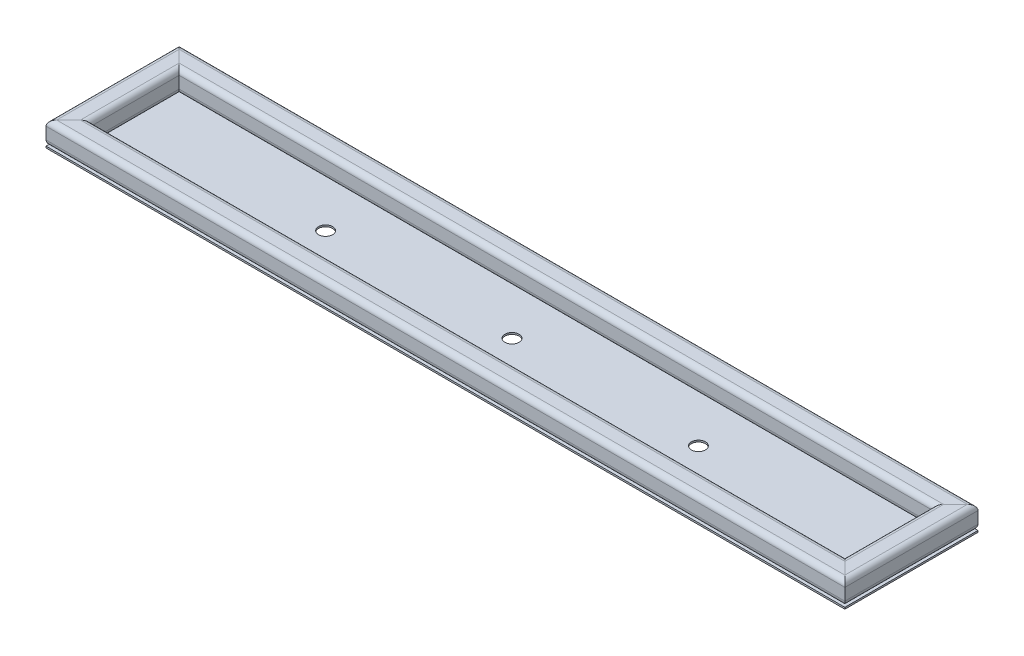
SolidWorks part; units mm, degrees
ref_plane "Alzado" through (0, 0, 0) normal (0, 0, 1) x (1, 0, 0)
ref_plane "Planta" through (0, 0, 0) normal (0, 1, 0) x (1, 0, 0)
ref_plane "Vista lateral" through (0, 0, 0) normal (1, 0, 0) x (0, 0, -1)
sketch "Croquis1" plane through (0, 0, 0) normal (0, 1, 0) x (1, 0, 0)
  line L1 (-450, 75) -> (450, 75)
  line L2 (-450, 75) -> (-450, -75)
  line L3 (-450, -75) -> (450, -75)
  line L4 (450, 75) -> (450, -75)
  line L5 (-450, 75) -> (450, -75) construction
  line L6 (-450, -75) -> (450, 75) construction
  point P0 (0, 0)
  dimension "D1" = 150
  dimension "D2" = 900
other "Tubo cuadrado 2 X 2 X 0.25(1)"
ref_plane "Plano1" through (-437.3, 12.7, -75) normal (0, 0, 1) x (1, 0, 0)
sketch "Sketch1" plane through (-437.3, 12.7, -75) normal (0, 0, 1) x (1, 0, 0)
  line L0 (-6.7, -9.7) -> (6.7, -9.7)
  line L1 (-9.7, -6.7) -> (-9.7, 6.7)
  line L2 (6.7, 9.7) -> (-6.7, 9.7)
  line L3 (9.7, 6.7) -> (9.7, -6.7)
  line L4 (-6.7, -12.7) -> (6.7, -12.7)
  line L5 (-12.7, -6.7) -> (-12.7, 6.7)
  line L6 (6.7, 12.7) -> (-6.7, 12.7)
  line L7 (12.7, 6.7) -> (12.7, -6.7)
  line L8 (0, 0) -> (9.7, 0) construction
  line L9 (0, 0) -> (0, 9.7) construction
  arc A0 (12.7, 6.7) -> (6.7, 12.7) centre (6.7, 6.7) ccw
  arc A1 (6.7, -12.7) -> (12.7, -6.7) centre (6.7, -6.7) ccw
  arc A2 (-12.7, -6.7) -> (-6.7, -12.7) centre (-6.7, -6.7) ccw
  arc A3 (-6.7, 12.7) -> (-12.7, 6.7) centre (-6.7, 6.7) ccw
  arc A4 (-6.7, 9.7) -> (-9.7, 6.7) centre (-6.7, 6.7) ccw
  arc A5 (9.7, 6.7) -> (6.7, 9.7) centre (6.7, 6.7) ccw
  arc A6 (6.7, -9.7) -> (9.7, -6.7) centre (6.7, -6.7) ccw
  arc A7 (-9.7, -6.7) -> (-6.7, -9.7) centre (-6.7, -6.7) ccw
  point P3 (0, 12.7)
  point P4 (12.7, 0)
  point P5 (0, -12.7)
  point P6 (-12.7, 0)
  point P7 (-12.7, 12.7)
  point P8 (-12.7, -12.7)
  point P33 (0, 0)
  point P35 (12.7, -12.7)
  point P36 (12.7, 12.7)
  point P37 (0, 0)
  dimension "D1" = 6
  dimension "Thickness" = 3
  dimension "V_leg" = 25.4
sketch "Croquis3" plane through (0, 0, 0) normal (0, -1, 0) x (1, 0, 0)
  line L1 (450, 75) -> (-450, 75)
  line L2 (450, 75) -> (450, -75)
  line L3 (450, -75) -> (-450, -75)
  line L4 (-450, 75) -> (-450, -75)
  line L5 (450, 75) -> (-450, -75) construction
  line L6 (450, -75) -> (-450, 75) construction
  point P0 (0, 0)
extrude "Saliente-Extruir1" add sketch "Croquis3" along normal blind 1.9 separate body
sketch "Croquis4" plane through (0, 0, 0) normal (0, 1, 0) x (1, 0, 0)
  circle A0 centre (-210, 0) radius 7.9375
  circle A3 centre (0, 0) radius 7.9375
  circle A6 centre (210, 0.0022) radius 7.9375
extrude "Cortar-Extruir1" cut sketch "Croquis4" against normal blind 10
